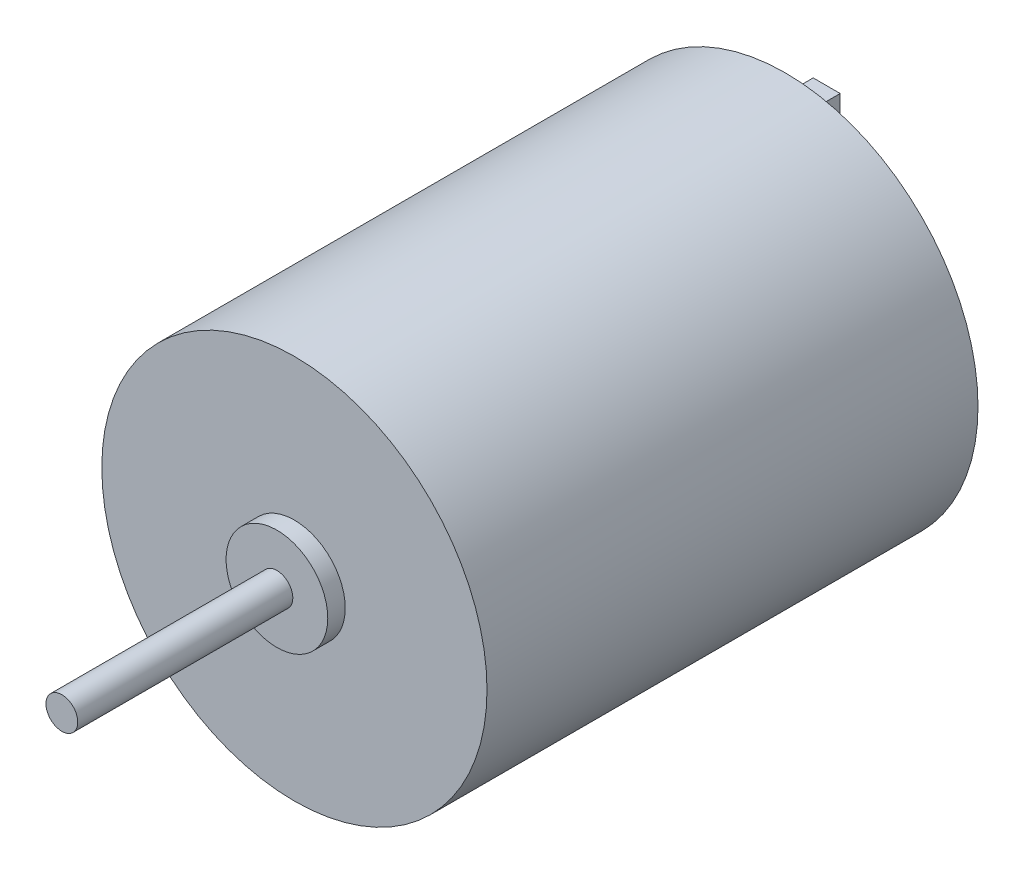
SolidWorks part; units mm, degrees
material "Alliage 1060"
ref_plane "Plan de face" through (0, 0, 0) normal (0, 0, 1) x (1, 0, 0)
ref_plane "Plan de dessus" through (0, 0, 0) normal (0, 1, 0) x (1, 0, 0)
ref_plane "Plan de droite" through (0, 0, 0) normal (1, 0, 0) x (0, 0, -1)
sketch "Esquisse1" plane through (0, 0, 0) normal (0, 0, 1) x (1, 0, 0)
  circle A0 centre (0, 0) radius 12.125
  dimension "D1" = 24.25
extrude "Boss.-Extru.1" add sketch "Esquisse1" along normal blind 30.91
sketch "Esquisse2" plane through (0, 0, 30.91) normal (0, 0, 1) x (1, 0, 0)
  circle A0 centre (0, 0) radius 3.2
  dimension "D1" = 6.4
extrude "Boss.-Extru.2" add sketch "Esquisse2" along normal blind 1.1
sketch "Esquisse3" plane through (0, 0, 32.01) normal (0, 0, 1) x (1, 0, 0)
  circle A0 centre (0, 0) radius 1
  dimension "D1" = 2
extrude "Boss.-Extru.3" add sketch "Esquisse3" along normal blind 13.54
sketch "Esquisse4" plane through (0, 0, 45.55) normal (0, 0, 1) x (1, 0, 0)
  line L0 (0.0796, 1.9484) -> (-0.185, 0.9827)
  line L1 (0.0796, 1.9484) -> (0.2646, 0.9644)
  line L2 (-0.185, 0.9827) -> (0.2646, 0.9644)
  line L3 (-0.185, 0.9827) -> (0.0376, 0.9217) construction
  line L4 (0.0376, 0.9217) -> (0.2646, 0.9644) construction
  line L5 (1.1774, 1.5545) -> (0.4327, 0.8852)
  line L6 (1.1774, 1.5545) -> (0.801, 0.6266)
  line L7 (0.4327, 0.8852) -> (0.801, 0.6266)
  line L8 (0.4327, 0.8852) -> (0.587, 0.7134) construction
  line L9 (0.587, 0.7134) -> (0.801, 0.6266) construction
  line L10 (1.8879, 0.6296) -> (0.8996, 0.4692)
  line L11 (1.8879, 0.6296) -> (1.0696, 0.0525)
  line L12 (0.8996, 0.4692) -> (1.0696, 0.0525)
  line L13 (0.8996, 0.4692) -> (0.9366, 0.2412) construction
  line L14 (0.9366, 0.2412) -> (1.0696, 0.0525) construction
  line L15 (1.9856, -0.5326) -> (1.0674, -0.1333)
  line L16 (1.9856, -0.5326) -> (0.9853, -0.5757)
  line L17 (1.0674, -0.1333) -> (0.9853, -0.5757)
  line L18 (1.0674, -0.1333) -> (0.9753, -0.345) construction
  line L19 (0.9753, -0.345) -> (0.9853, -0.5757) construction
  line L20 (1.4395, -1.5632) -> (0.883, -0.7308)
  line L21 (1.4395, -1.5632) -> (0.5746, -1.0586)
  line L22 (0.883, -0.7308) -> (0.5746, -1.0586)
  line L23 (0.883, -0.7308) -> (0.691, -0.8591) construction
  line L24 (0.691, -0.8591) -> (0.5746, -1.0586) construction
  line L25 (0.4229, -2.1348) -> (0.4047, -1.1337)
  line L26 (0.4229, -2.1348) -> (-0.0319, -1.2428)
  line L27 (0.4047, -1.1337) -> (-0.0319, -1.2428)
  line L28 (0.4047, -1.1337) -> (0.1739, -1.1379) construction
  line L29 (0.1739, -1.1379) -> (-0.0319, -1.2428) construction
  line L30 (-0.7414, -2.0661) -> (-0.2154, -1.2142)
  line L31 (-0.7414, -2.0661) -> (-0.6417, -1.0699)
  line L32 (-0.2154, -1.2142) -> (-0.6417, -1.0699)
  line L33 (-0.2154, -1.2142) -> (-0.4119, -1.0929) construction
  line L34 (-0.4119, -1.0929) -> (-0.6417, -1.0699) construction
  line L35 (-1.6837, -1.3789) -> (-0.7806, -0.9465)
  line L36 (-1.6837, -1.3789) -> (-1.0612, -0.5947)
  line L37 (-0.7806, -0.9465) -> (-1.0612, -0.5947)
  line L38 (-0.7806, -0.9465) -> (-0.8804, -0.7383) construction
  line L39 (-0.8804, -0.7383) -> (-1.0612, -0.5947) construction
  line L40 (-2.1049, -0.2913) -> (-1.1114, -0.4158)
  line L41 (-2.1049, -0.2913) -> (-1.1572, 0.0318)
  line L42 (-1.1114, -0.4158) -> (-1.1572, 0.0318)
  line L43 (-1.1114, -0.4158) -> (-1.0827, -0.1867) construction
  line L44 (-1.0827, -0.1867) -> (-1.1572, 0.0318) construction
  line L45 (-1.8712, 0.8513) -> (-1.1028, 0.2095)
  line L46 (-1.8712, 0.8513) -> (-0.8993, 0.6108)
  line L47 (-1.1028, 0.2095) -> (-0.8993, 0.6108)
  line L48 (-1.1028, 0.2095) -> (-0.9548, 0.3867) construction
  line L49 (-0.9548, 0.3867) -> (-0.8993, 0.6108) construction
  line L50 (-1.0569, 1.6863) -> (-0.7574, 0.7308)
  line L51 (-1.0569, 1.6863) -> (-0.3693, 0.9585)
  line L52 (-0.7574, 0.7308) -> (-0.3693, 0.9585)
  line L53 (-0.7574, 0.7308) -> (-0.5371, 0.7999) construction
  line L54 (-0.5371, 0.7999) -> (-0.3693, 0.9585) construction
  circle A0 centre (0, 0) radius 1.95 construction
  circle A1 centre (0, 0) radius 1 construction
  circle A2 centre (0, 0) radius 1 construction
  circle A3 centre (0, 0) radius 1 construction
  point P55 (-0.0423, -0.1179)
  dimension "D1" = 3.9
  dimension "D2" = 0.45
  dimension "D3" = 11
extrude "Boss.-Extru.4" [suppressed] add sketch "Esquisse4" along normal blind 3.15 separate body contours L1 L2 L0
sketch "Esquisse8" plane through (0, 0, 45.55) normal (0, 0, 1) x (1, 0, 0)
  circle A0 centre (0, 0) radius 0.865
extrude "Boss.-Extru.5" [suppressed] add sketch "Esquisse8" along normal blind 3.15
sketch "Esquisse9" plane through (0, 0, 0) normal (0, 0, -1) x (-1, 0, 0)
  line L0 (0, 12.125) -> (0, -12.125) construction
  line L2 (-0.85, -10.125) -> (0.85, -10.125)
  line L3 (-0.85, -10.125) -> (-0.85, -8.425)
  line L4 (-0.85, -8.425) -> (0.85, -8.425)
  line L5 (0.85, -10.125) -> (0.85, -8.425)
  line L6 (-0.85, -10.125) -> (0.85, -8.425) construction
  line L7 (-0.85, -8.425) -> (0.85, -10.125) construction
  line L8 (-0.85, 8.425) -> (0.85, 8.425)
  line L9 (-0.85, 8.425) -> (-0.85, 10.125)
  line L10 (-0.85, 10.125) -> (0.85, 10.125)
  line L11 (0.85, 8.425) -> (0.85, 10.125)
  line L12 (-0.85, 8.425) -> (0.85, 10.125) construction
  line L13 (-0.85, 10.125) -> (0.85, 8.425) construction
  circle A0 centre (0, 0) radius 12.125 construction
  point P5 (0, -9.275)
  point P10 (0, 9.275)
  dimension "D1" = 2
  dimension "D2" = 1.7
  dimension "D3" = 2
extrude "Boss.-Extru.6" add sketch "Esquisse9" along normal blind 2.6
